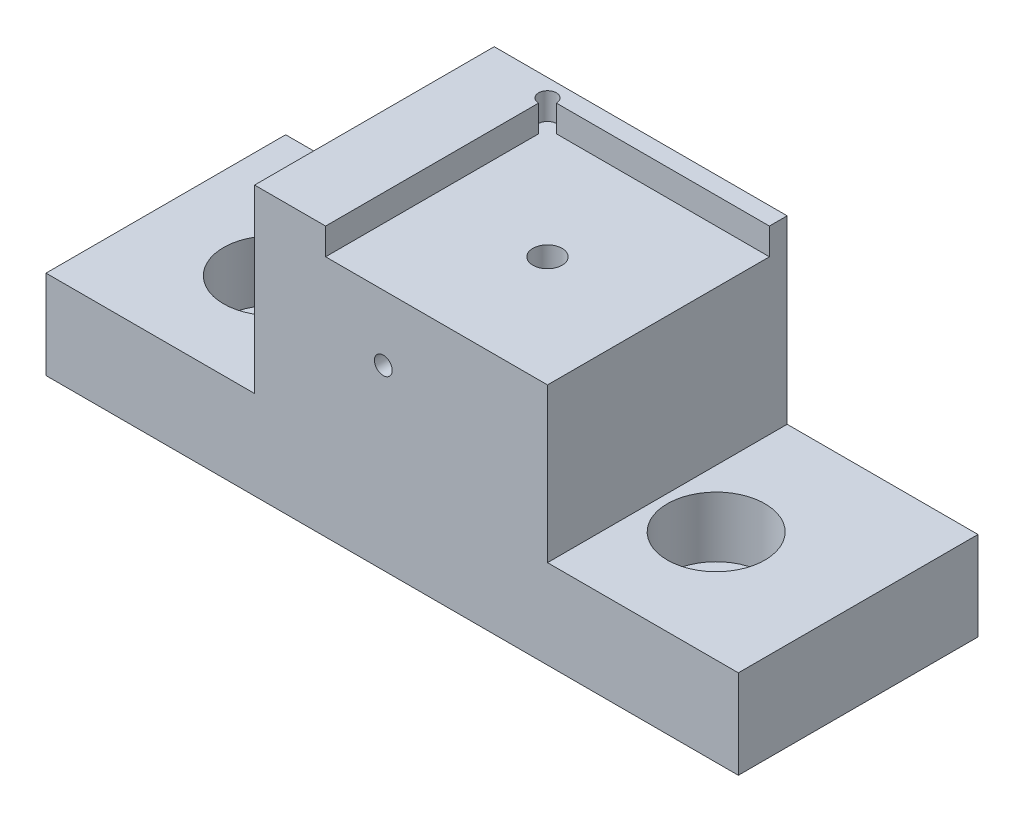
SolidWorks part; units mm, degrees
material "6061 合金"
ref_plane "前视基准面" through (0, 0, 0) normal (0, 0, 1) x (1, 0, 0)
ref_plane "上视基准面" through (0, 0, 0) normal (0, 1, 0) x (1, 0, 0)
ref_plane "右视基准面" through (0, 0, 0) normal (1, 0, 0) x (0, 0, -1)
sketch "草图1" plane through (0, 0, 0) normal (0, 1, 0) x (1, 0, 0)
  line L1 (-14.5, 14.5) -> (14.5, 14.5)
  line L2 (-14.5, 14.5) -> (-14.5, -14.5)
  line L3 (-14.5, -14.5) -> (14.5, -14.5)
  line L4 (14.5, 14.5) -> (14.5, -14.5)
  line L5 (-14.5, 14.5) -> (14.5, -14.5) construction
  line L6 (-14.5, -14.5) -> (14.5, 14.5) construction
  point P0 (0, 0)
  dimension "D1" = 29
  dimension "D2" = 29
extrude "凸台-拉伸1" add sketch "草图1" along normal blind 5
sketch "草图2" plane through (0, 5, 0) normal (0, -1, 0) x (1, 0, 0)
  line L1 (-12.5, 12.5) -> (12.5, 12.5)
  line L2 (-12.5, 12.5) -> (-12.5, -12.5)
  line L3 (-12.5, -12.5) -> (12.5, -12.5)
  line L4 (12.5, 12.5) -> (12.5, -12.5)
  line L5 (-12.5, 12.5) -> (12.5, -12.5) construction
  line L6 (-12.5, -12.5) -> (12.5, 12.5) construction
  point P0 (0, 0)
  dimension "D1" = 25
  dimension "D2" = 25
extrude "切除-拉伸1" cut sketch "草图2" along normal blind 3
sketch "草图3" plane through (0, 0, 0) normal (0, -1, 0) x (-1, 0, 0)
  line L1 (-14.5, -14.5) -> (20.5, -14.5)
  line L2 (-14.5, -14.5) -> (-14.5, 14.5)
  line L3 (-14.5, 14.5) -> (20.5, 14.5)
  line L4 (20.5, -14.5) -> (20.5, 14.5)
  dimension "D1" = 29
  dimension "D2" = 35
extrude "拉到底部滑块" add sketch "草图3" along normal up to surface (25.3412 mm away)
sketch "草图5" plane through (0, 2, 0) normal (0, 1, 0) x (1, 0, 0)
  circle A0 centre (0, 0) radius 2.1526
hole_wizard "M4 螺纹孔1" positions "3D草图1" profile "草图6" tap size "M4" standard "GB"
sketch3d "3D草图1"
  point P0 (0, 2, 0)
sketch "草图6" plane through (0, 2, 0) normal (1, 0, 0) x (0, 0, 1)
  line L0 (0, 0) -> (0, 11.0914)
  line L1 (0, 11.0914) -> (1.65, 10.1)
  line L2 (1.65, 10.1) -> (1.65, 0)
  line L5 (1.65, 0) -> (0, 0)
  line L10 (0, 11.0914) -> (-1.65, 10.1) construction
  line L11 (0, -6.35) -> (0, 107.95) construction
  dimension "螺纹孔钻头直径" = 3.3
  dimension "螺纹孔钻头深度" = 10.1
  dimension "导头角度" = 118
cosmetic thread "孔螺蚊线1" parameters "D1"=8, "D2"=4
sketch "草图9" plane through (0, 5, 0) normal (0, 1, 0) x (1, 0, 0)
  circle A0 centre (-12.5, 12.5) radius 1
extrude "切除-拉伸2" cut sketch "草图9" against normal up to surface (3 mm away) up to face at (0, 2, 1.65)
sketch "草图11" plane through (-14.5, 0, 0) normal (-1, 0, 0) x (0, 0, 1)
  line L4 (-14.5, 0) -> (14.5, 0)
  line L5 (14.5, 0) -> (14.5, 5)
  line L6 (14.5, 5) -> (-14.5, 5)
  line L7 (-14.5, 5) -> (-14.5, 0)
  line L8 (-14.5, 0) -> (14.5, 0)
  line L9 (14.5, 0) -> (14.5, 5)
  line L10 (14.5, 5) -> (-14.5, 5)
  line L11 (-14.5, 5) -> (-14.5, 0)
  dimension "D1" = 0
extrude "凸台-拉伸4" add sketch "草图11" along normal up to surface (6 mm away) up to face at (-20.5, -12.6706, 0)
sketch "草图17" plane through (0, 5, 0) normal (0, 1, 0) x (1, 0, 0)
  line L0 (-20.5, -14.5) -> (14.5, -14.5) construction
  line L1 (14.5, -14.5) -> (14.5, 14.5) construction
  line L2 (-20.5, -14.5) -> (14.5, -14.5)
  line L3 (14.5, -14.5) -> (14.5, 14.5)
  line L4 (-20.5, -12.5) -> (12.5, -12.5)
  line L5 (12.5, -12.5) -> (12.5, 14.5)
  line L6 (12.5, 14.5) -> (14.5, 14.5)
  line L7 (-20.5, -12.5) -> (-20.5, -14.5)
  dimension "D1" = 2
extrude "切除-拉伸8" cut sketch "草图17" against normal through all
sketch "草图18" plane through (0, -25.3412, 0) normal (0, -1, 0) x (1, 0, 0)
  line L0 (0, 0) -> (-6, 0) construction
  line L1 (16.5, 0) -> (-16.5, 0) construction
  line L2 (-6, 0) -> (-6, 12.5) construction
  line L3 (12.5, 12.5) -> (-20.5, 12.5) construction
  circle A0 centre (-6, 0) radius 1.512
  dimension "D1" = 6
sketch "草图19" plane through (0, -25.3412, 0) normal (0, -1, 0) x (-1, 0, 0)
  line L0 (-12.5, -12.5) -> (20.5, -12.5) construction
  line L1 (46, -12.5) -> (-34, -12.5)
  line L2 (46, -12.5) -> (46, 12.5)
  line L3 (46, 12.5) -> (-34, 12.5)
  line L4 (-34, -12.5) -> (-34, 12.5)
  line L5 (46, -12.5) -> (-34, 12.5) construction
  line L6 (46, 12.5) -> (-34, -12.5) construction
  point P0 (6, 0)
  dimension "D1" = 80
extrude "凸台-拉伸5" add sketch "草图19" against normal blind 10
sketch "草图21" plane through (0, -15.3412, 0) normal (0, 1, 0) x (1, 0, 0)
  line L0 (-6, 0) -> (-31, 0)
  line L3 (-16.5, 0) -> (16.5, 0) construction
  line L4 (-6, 0) -> (19, 0)
  dimension "D1" = 25
  dimension "D2" = 25
hole_wizard "打孔尺寸(%根据)内六角圆柱头螺钉的类型1" positions "3D草图2" profile "草图22" counterbore size "M6" standard "GB"
sketch3d "3D草图2"
  point P0 (-31, -15.3412, 0)
  point P3 (19, -15.3412, 0)
sketch "草图22" plane through (-31, -15.3412, 0) normal (1, 0, 0) x (0, 0, 1)
  line L0 (0, 0) -> (0, 12.0828)
  line L1 (0, 12.0828) -> (3.3, 10.1)
  line L2 (3.3, 10.1) -> (3.3, 6.8)
  line L3 (3.3, 6.8) -> (5.5, 6.8)
  line L4 (5.5, 6.8) -> (5.5, 0)
  line L5 (5.5, 0) -> (0, 0)
  line L10 (0, 12.0828) -> (-3.3, 10.1) construction
  line L11 (0, -6.35) -> (0, 107.95) construction
  dimension "孔直径" = 6.6
  dimension "孔深度" = 10.1
  dimension "柱形沉头孔直径" = 11
  dimension "柱形沉头孔深度" = 6.8
  dimension "导头角度" = 118
sketch "草图23" plane through (0, 0, -12.5) normal (0, 0, -1) x (-1, 0, 0)
  line L1 (-34, -15.3412) -> (46, -15.3412)
  line L2 (-34, -15.3412) -> (-34, -25.3412)
  line L3 (-34, -25.3412) -> (46, -25.3412)
  line L4 (46, -15.3412) -> (46, -25.3412)
extrude "凸台-拉伸6" add sketch "草图23" along normal up to surface (2 mm away) up to face at (-4, -10.1706, -14.5)
sketch "草图24" plane through (-46, 0, 0) normal (-1, 0, 0) x (0, 0, 1)
  line L4 (-14.5, -25.3412) -> (12.5, -25.3412)
  line L5 (12.5, -25.3412) -> (12.5, -15.3412)
  line L6 (12.5, -15.3412) -> (-14.5, -15.3412)
  line L7 (-14.5, -15.3412) -> (-14.5, -25.3412)
  line L8 (-14.5, -25.3412) -> (12.5, -25.3412)
  line L9 (12.5, -25.3412) -> (12.5, -15.3412)
  line L10 (12.5, -15.3412) -> (-14.5, -15.3412)
  line L11 (-14.5, -15.3412) -> (-14.5, -25.3412)
  dimension "D1" = 0
extrude "切除-拉伸9" cut sketch "草图24" against normal blind 2
sketch "草图25" plane through (0, -25.3412, 0) normal (0, -1, 0) x (1, 0, 0)
  line L0 (-31, 0) -> (-16, 0) construction
  line L1 (-6, 0) -> (-31, 0) construction
  line L2 (19, 0) -> (4, 0) construction
  line L3 (-6, 0) -> (19, 0) construction
  dimension "D1" = 15
hole_wizard "大小mm 暗销孔1" positions "3D草图3" profile "草图26" hole size "Ø4.0" standard "GB"
sketch3d "3D草图3"
  point P0 (-16, -25.3412, 0)
sketch "草图26" plane through (-16, -25.3412, 0) normal (1, 0, 0) x (0, 0, -1)
  line L0 (0, 0) -> (0, 6.2017)
  line L1 (0, 6.2017) -> (2, 5)
  line L2 (2, 5) -> (2, 0)
  line L5 (2, 0) -> (0, 0)
  line L10 (0, 6.2017) -> (-2, 5) construction
  line L11 (0, -6.35) -> (0, 107.95) construction
  dimension "孔直径" = 4
  dimension "孔深度" = 5
  dimension "导头角度" = 118
sketch "草图27" plane through (0, -25.3412, 0) normal (0, -1, 0) x (1, 0, 0)
  line L0 (3.5, 0) -> (4.5, 0) construction
  line L1 (3.5, 2) -> (4.5, 2)
  line L2 (3.5, -2) -> (4.5, -2)
  arc A0 (3.5, 2) -> (3.5, -2) centre (3.5, 0) ccw
  arc A1 (4.5, -2) -> (4.5, 2) centre (4.5, 0) ccw
  circle A2 centre (-16, 0) radius 2 construction
  point P2 (4, 0)
  dimension "D1" = 1
extrude "切除-拉伸10" cut sketch "草图27" against normal blind 5
sketch "草图28" plane through (0, 0, 12.5) normal (0, 0, 1) x (1, 0, 0)
  line L0 (-6, -25.3412) -> (-6, -5.3412) construction
  circle A0 centre (-6, -5.3412) radius 1
  dimension "D1" = 20
extrude "切除-拉伸11" cut sketch "草图28" against normal blind 2
hole_wizard "M6 螺纹孔1" positions "3D草图4" profile "草图29" tap size "M6" standard "GB"
sketch3d "3D草图4"
  point P0 (-6, -25.3412, 0)
sketch "草图29" plane through (-6, -25.3412, 0) normal (1, 0, 0) x (0, 0, -1)
  line L0 (0, 0) -> (0, 11.5022)
  line L1 (0, 11.5022) -> (2.5, 10)
  line L2 (2.5, 10) -> (2.5, 0)
  line L5 (2.5, 0) -> (0, 0)
  line L10 (0, 11.5022) -> (-2.5, 10) construction
  line L11 (0, -6.35) -> (0, 107.95) construction
  dimension "螺纹孔钻头直径" = 5
  dimension "螺纹孔钻头深度" = 10
  dimension "导头角度" = 118
cosmetic thread "孔螺蚊线2" parameters "D1"=10, "D2"=6
sketch "草图30" plane through (0, -25.3412, 0) normal (0, -1, 0) x (-1, 0, 0)
  circle A0 centre (16, 0) radius 2
  circle A1 centre (-4, 0) radius 2
